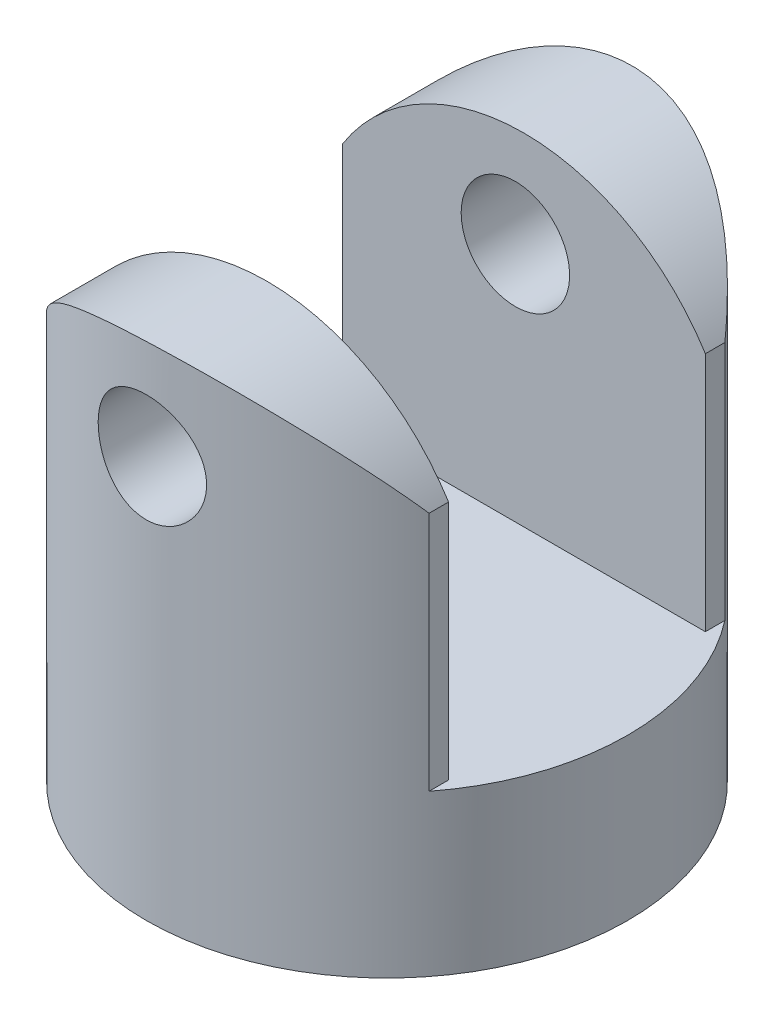
SolidWorks part; units mm, degrees
ref_plane "Front Plane" through (0, 0, 0) normal (0, 0, 1) x (1, 0, 0)
ref_plane "Top Plane" through (0, 0, 0) normal (0, 1, 0) x (1, 0, 0)
ref_plane "Right Plane" through (0, 0, 0) normal (1, 0, 0) x (0, 0, -1)
sketch "Sketch1" plane through (0, 0, 0) normal (0, 1, 0) x (1, 0, 0)
  circle A0 centre (0, 0) radius 15
  dimension "D1" = 30
extrude "Boss-Extrude1" add sketch "Sketch1" along normal blind 10
sketch "Sketch2" plane through (0, 0, 0) normal (0, 0, 1) x (1, 0, 0)
  line L0 (-10.7808, 10) -> (11.8369, 10)
  line L1 (15, 10) -> (-15, 10) construction
  line L2 (11.8369, 10) -> (11.8369, 25)
  line L4 (-10.7808, 25) -> (-10.7808, 10)
  arc A0 (-10.7808, 25) -> (11.8369, 25) centre (0.528, 17.9078) cw
  dimension "D1" = 15
extrude "Boss-Extrude2" add sketch "Sketch2" along normal up to surface and the other way up to surface up to face at (0, 10, 15) other way up to face at (0, 10, 15)
sketch "Sketch3" plane through (11.8369, 0, 0) normal (1, 0, 0) x (0, 0, -1)
  line L0 (9.2135, 10) -> (-9.2135, 10) construction
  line L1 (-8, 10) -> (8, 10)
  line L2 (-8, 10) -> (-8, 60)
  line L3 (-8, 60) -> (8, 60)
  line L4 (8, 10) -> (8, 60)
  line L5 (0, 0) -> (0, 10) construction
  dimension "D1" = 16
  dimension "D2" = 50
extrude "Cut-Extrude1" cut sketch "Sketch3" against normal through all
sketch "Sketch4" plane through (0, 0, 8) normal (0, 0, -1) x (-1, 0, 0)
  circle A0 centre (0, 25) radius 3.3782
extrude "Cut-Extrude2" cut sketch "Sketch4" against normal through all and the other way through all
